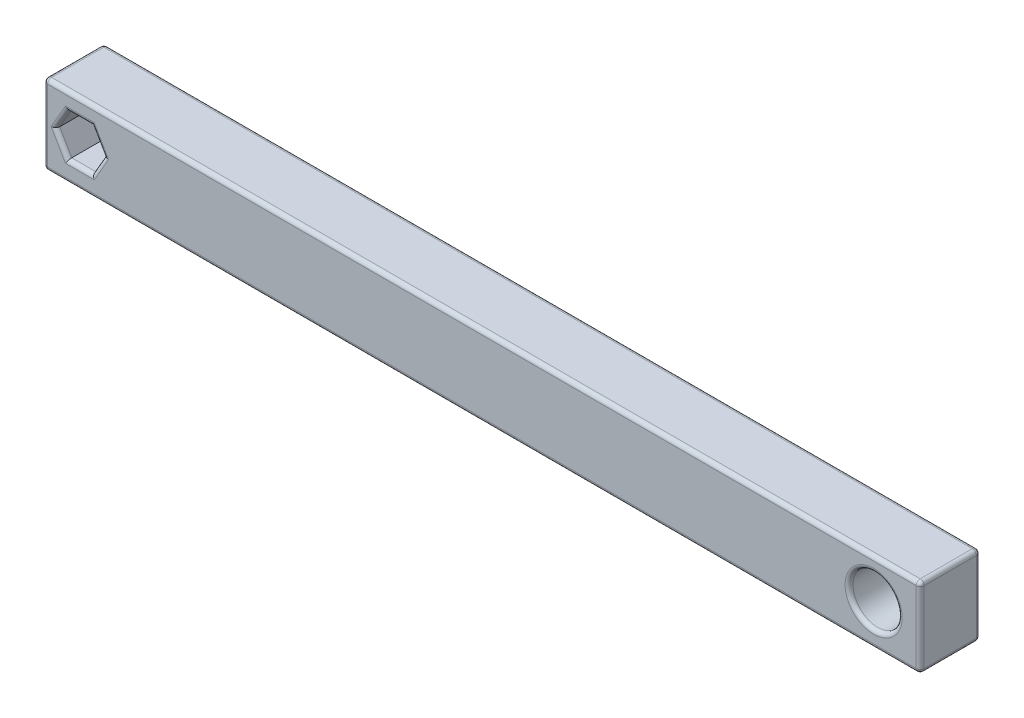
SolidWorks part; units mm, degrees
ref_plane "Front Plane" through (0, 0, 0) normal (0, 0, 1) x (1, 0, 0)
ref_plane "Top Plane" through (0, 0, 0) normal (0, 1, 0) x (1, 0, 0)
ref_plane "Right Plane" through (0, 0, 0) normal (1, 0, 0) x (0, 0, -1)
sketch "Sketch1" plane through (0, 0, 0) normal (0, 0, 1) x (1, 0, 0)
  line L1 (-29.1771, 46.211) -> (529.6229, 46.211)
  line L2 (-29.1771, 46.211) -> (-29.1771, -4.589)
  line L3 (-29.1771, -4.589) -> (529.6229, -4.589)
  line L4 (529.6229, 46.211) -> (529.6229, -4.589)
  line L5 (9.2665, 21.5059) -> (1.582, 34.816)
  line L6 (1.582, 34.816) -> (-13.7871, 34.816)
  line L7 (-13.7871, 34.816) -> (-21.4717, 21.5059)
  line L8 (-21.4717, 21.5059) -> (-13.7871, 8.1959)
  line L9 (-13.7871, 8.1959) -> (1.582, 8.1959)
  line L10 (1.582, 8.1959) -> (9.2665, 21.5059)
  circle A0 centre (-6.1026, 21.5059) radius 13.3101 construction
  circle A1 centre (499.9402, 21.5059) radius 15.6615
  dimension "D1" = 558.8
  dimension "D2" = 50.8
extrude "Boss-Extrude1" add sketch "Sketch1" along normal blind 38.354
fillet "Fillet2" radius 2.54 1 edges at (-29.1771, 46.211, 19.177)
fillet "Fillet3" radius 2.54 3 edges at (251.4929, 46.211, 38.354) (-29.1771, 19.541, 38.354) (-28.4331, 45.4671, 38.354)
fillet "Fillet4" radius 2.54 3 edges at (-29.1771, 19.541, 0) (251.4929, 46.211, 0) (-28.4331, 45.4671, 0)
fillet "Fillet5" radius 2.54 5 edges at (529.6229, 19.541, 0) (529.6229, 19.541, 38.354) (529.6229, 46.211, 19.177) (529.6229, 45.4671, 37.6101) (529.6229, 45.4671, 0.7439)
fillet "Fillet6" radius 2.54 8 edges at (250.2229, -4.589, 38.354) (528.879, -4.589, 37.6101) (529.6229, -4.589, 19.177) (528.879, -4.589, 0.7439) (250.2229, -4.589, 0) (-28.4331, -4.589, 0.7439) (-29.1771, -4.589, 19.177) (-28.4331, -4.589, 37.6101)
fillet "Fillet7" radius 2.54 2 edges at (515.6017, 21.5059, 0) (515.6017, 21.5059, 38.354)
fillet "Fillet8" radius 2.54 6 edges at (5.4243, 14.8509, 0) (-6.1026, 8.1959, 0) (-17.6294, 14.8509, 0) (-17.6294, 28.1609, 0) (-6.1026, 34.816, 0) (5.4243, 28.1609, 0)
fillet "Fillet9" radius 2.54 6 edges at (-17.6294, 28.1609, 38.354) (-17.6294, 14.8509, 38.354) (-6.1026, 8.1959, 38.354) (5.4243, 14.8509, 38.354) (5.4243, 28.1609, 38.354) (-6.1026, 34.816, 38.354)
